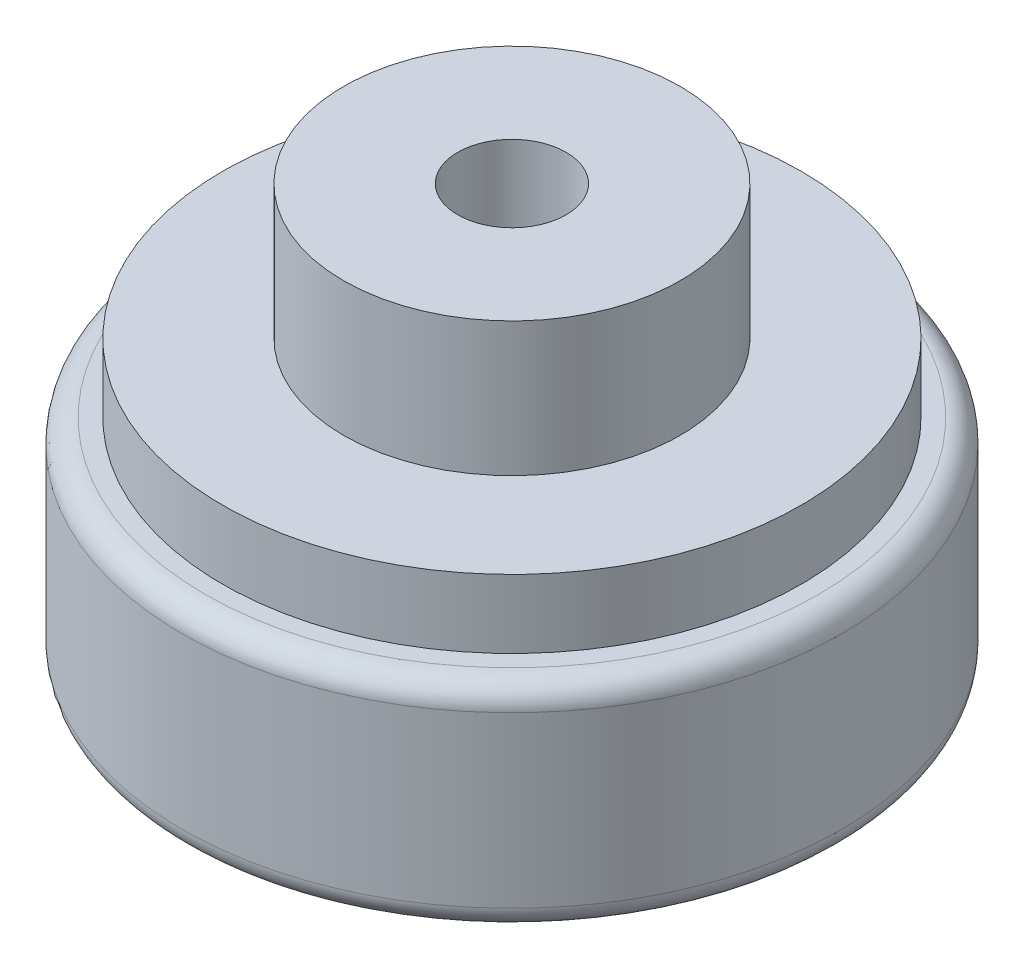
SolidWorks part; units mm, degrees
ref_plane "Front Plane" through (0, 0, 0) normal (0, 0, 1) x (1, 0, 0)
ref_plane "Top Plane" through (0, 0, 0) normal (0, 1, 0) x (1, 0, 0)
ref_plane "Right Plane" through (0, 0, 0) normal (1, 0, 0) x (0, 0, -1)
sketch "Sketch1" plane through (0, 0, 0) normal (0, 0, 1) x (1, 0, 0)
  line L0 (0, 0) -> (0, 37.1739) construction
  line L1 (6.0325, 22.5298) -> (6.0325, 0)
  line L2 (6.0325, 22.5298) -> (18.7325, 22.5298)
  line L3 (18.7325, 22.5298) -> (18.7325, 7.62)
  line L4 (18.7325, 7.62) -> (32.1945, 7.62)
  line L5 (6.0325, 0) -> (32.1945, 0)
  line L6 (32.1945, 0) -> (32.1945, 7.62)
  line L7 (6.0325, 0) -> (6.0325, -23.9268)
  line L8 (6.0325, -23.9268) -> (34.1376, -23.9268)
  line L9 (36.6776, -21.3868) -> (36.6776, -2.54)
  line L10 (34.1376, 0) -> (32.1945, 0)
  arc A0 (34.1376, -23.9268) -> (36.6776, -21.3868) centre (34.1376, -21.3868) ccw
  arc A1 (36.6776, -2.54) -> (34.1376, 0) centre (34.1376, -2.54) ccw
  dimension "D8" = 2.54
  dimension "D1" = 7.62
  dimension "D2" = 12.7
  dimension "D3" = 6.0325
  dimension "D4" = 26.162
  dimension "D5" = 14.9098
  dimension "D6" = 23.9268
  dimension "D7" = 36.6776
revolve "Revolve1" add sketch "Sketch1" angle 360 about L0
